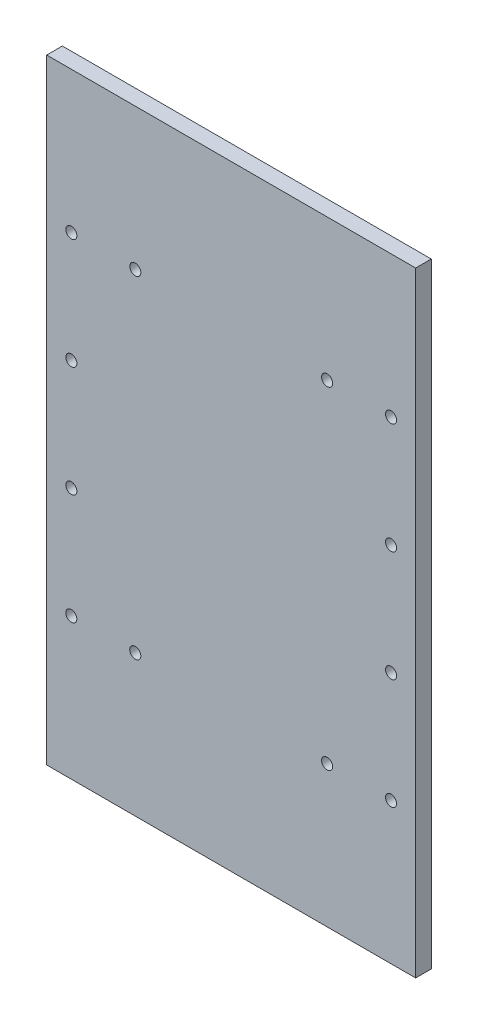
SolidWorks part; units mm, degrees
material "Acrylic (Medium-high impact)"
ref_plane "Front Plane" through (0, 0, 0) normal (0, 0, 1) x (1, 0, 0)
ref_plane "Top Plane" through (0, 0, 0) normal (0, 1, 0) x (1, 0, 0)
ref_plane "Right Plane" through (0, 0, 0) normal (1, 0, 0) x (0, 0, -1)
sketch "Sketch1" plane through (0, 0, 0) normal (0, 0, 1) x (1, 0, 0)
  line L1 (0, 0) -> (150, 0)
  line L2 (0, 0) -> (0, 250)
  line L3 (0, 250) -> (150, 250)
  line L4 (150, 0) -> (150, 250)
  dimension "D1" = 150
  dimension "D2" = 250
extrude "Boss-Extrude1" add sketch "Sketch1" along normal blind 6.35
hole_wizard "M4 Clearance Hole1" positions "Sketch2" profile "Sketch3" hole size "M4" standard "ANSI Metric" end condition through all
sketch "Sketch2" plane through (0, 0, 6.35) normal (0, 0, 1) x (1, 0, 0)
  line L0 (140, 250) -> (140, 0) construction
  line L1 (150, 250) -> (0, 250) construction
  line L2 (0, 0) -> (150, 0) construction
  line L4 (150, 0) -> (150, 250) construction
  line L6 (10, 250) -> (10, 0) construction
  line L8 (0, 250) -> (0, 0) construction
  line L9 (10, 192.5) -> (140, 192.5) construction
  line L11 (10, 147.5) -> (140, 147.5) construction
  line L13 (10, 102.5) -> (140, 102.5) construction
  line L14 (10, 57.5) -> (140, 57.5) construction
  line L16 (75, 147.5) -> (75, 102.5) construction
  line L18 (0, 125) -> (75, 125) construction
  point P0 (10, 192.5)
  point P2 (10, 147.5)
  point P4 (10, 102.5)
  point P6 (140, 192.5)
  point P8 (140, 147.5)
  point P10 (140, 102.5)
  point P47 (10, 57.5)
  point P49 (140, 57.5)
  dimension "D1" = 10
  dimension "D2" = 10
  dimension "D3" = 45
  dimension "D4" = 45
  dimension "D5" = 45
sketch "Sketch3" plane through (10, 192.5, 6.35) normal (1, 0, 0) x (0, -1, 0)
  line L0 (0, 0) -> (0, 6.35)
  line L1 (0, 6.35) -> (2.25, 6.35)
  line L2 (2.25, 6.35) -> (2.25, 0)
  line L5 (2.25, 0) -> (0, 0)
  line L11 (0, -6.35) -> (0, 107.95) construction
  dimension "Thru Hole Dia." = 4.5
  dimension "Thru Hole Depth" = 6.35
hole_wizard "M4 Clearance Hole2" positions "Sketch4" profile "Sketch5" hole size "M4" standard "ANSI Metric" end condition through all
sketch "Sketch4" plane through (0, 0, 6.35) normal (0, 0, 1) x (1, 0, 0)
  line L0 (36, 192.5) -> (114, 192.5) construction
  line L1 (114, 192.5) -> (114, 57.5) construction
  line L2 (114, 57.5) -> (36, 57.5) construction
  line L3 (36, 57.5) -> (36, 192.5) construction
  line L5 (0, 250) -> (0, 0) construction
  line L8 (10, 57.5) -> (140, 57.5) construction
  line L10 (10, 192.5) -> (140, 192.5) construction
  point P0 (36, 57.5)
  point P2 (36, 192.5)
  point P4 (114, 192.5)
  point P6 (114, 57.5)
  dimension "D1" = 36
  dimension "D2" = 78
sketch "Sketch5" plane through (36, 57.5, 6.35) normal (1, 0, 0) x (0, -1, 0)
  line L0 (0, 0) -> (0, 6.35)
  line L1 (0, 6.35) -> (2.25, 6.35)
  line L2 (2.25, 6.35) -> (2.25, 0)
  line L5 (2.25, 0) -> (0, 0)
  line L11 (0, -6.35) -> (0, 107.95) construction
  dimension "Thru Hole Dia." = 4.5
  dimension "Thru Hole Depth" = 6.35
